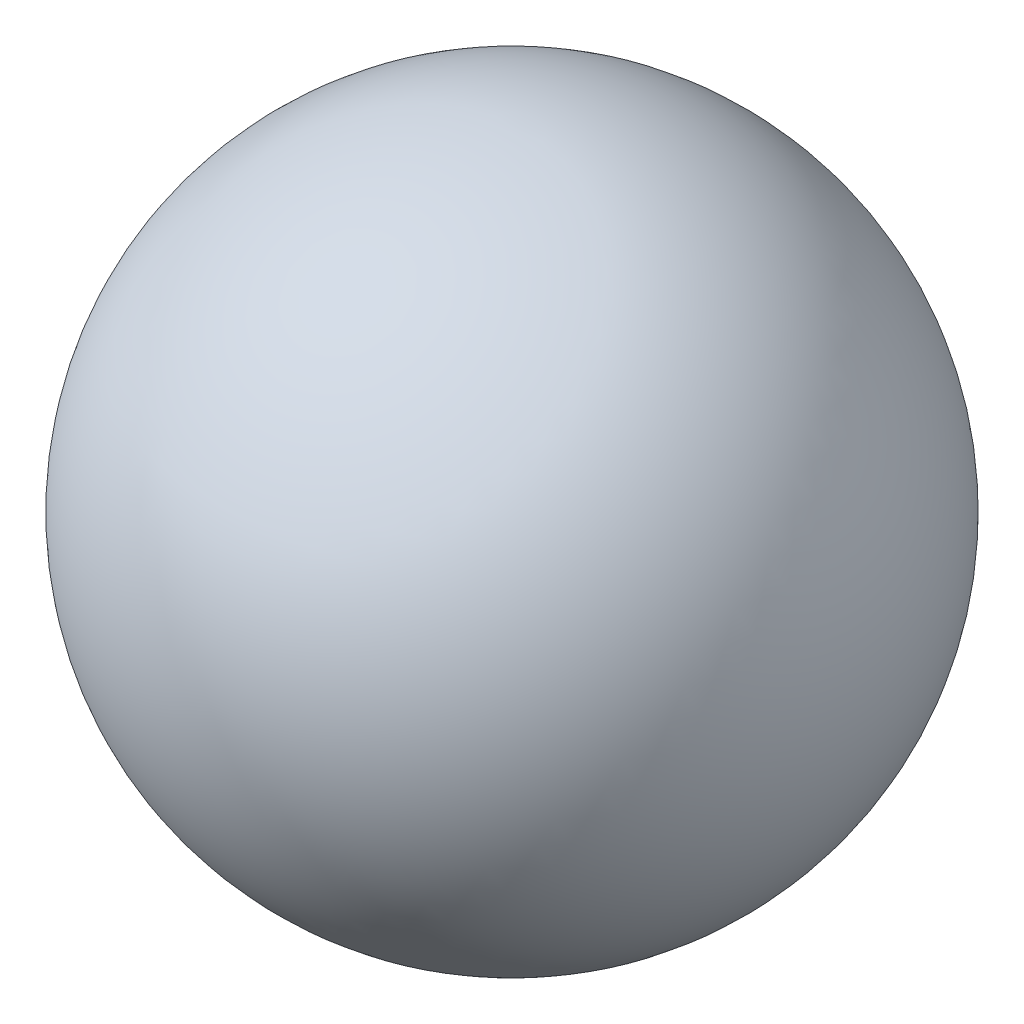
SolidWorks part; units mm, degrees
ref_plane "Front Plane" through (0, 0, 0) normal (0, 0, 1) x (1, 0, 0)
ref_plane "Top Plane" through (0, 0, 0) normal (0, 1, 0) x (1, 0, 0)
ref_plane "Right Plane" through (0, 0, 0) normal (1, 0, 0) x (0, 0, -1)
sketch "Sketch1" plane through (0, 0, 0) normal (0, 0, 1) x (1, 0, 0)
  line L0 (0, 0) -> (0, 11.5)
  arc A0 (0, 11.5) -> (0, 0) centre (0, 5.75) cw
  dimension "D1" = 11.5
revolve "Revolve1" add sketch "Sketch1" angle 360 about L0
